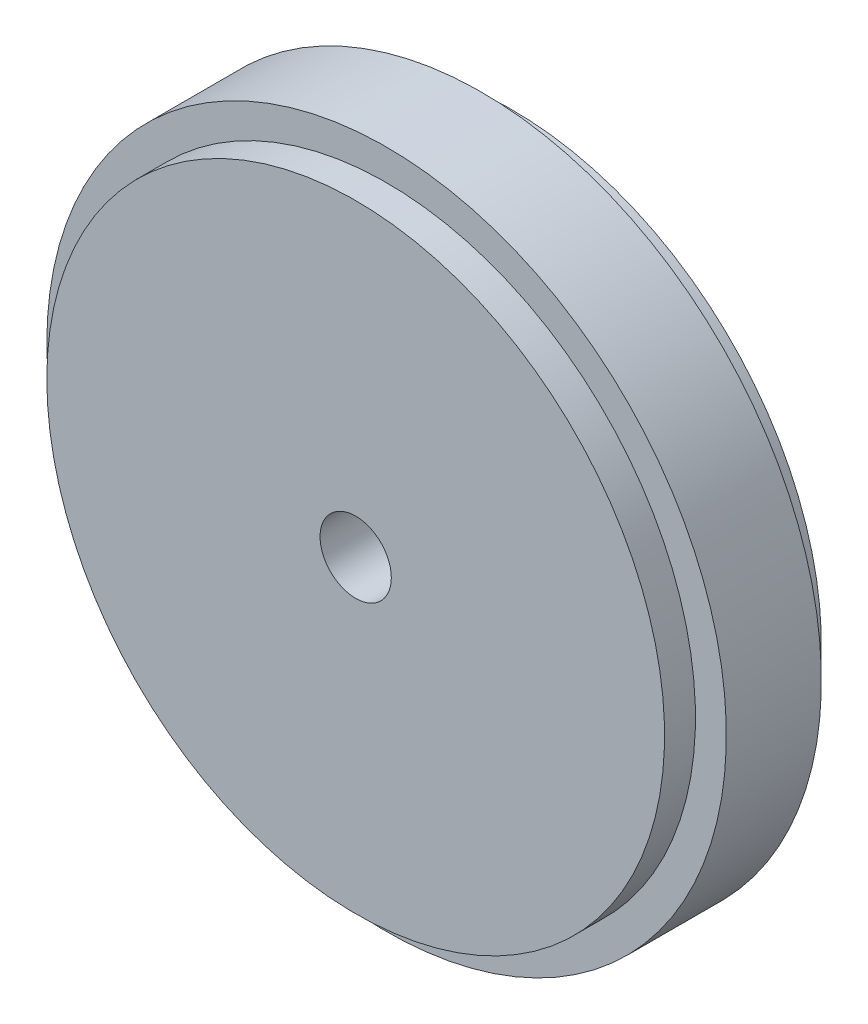
SolidWorks part; units mm, degrees
ref_plane "Front Plane" through (0, 0, 0) normal (0, 0, 1) x (1, 0, 0)
ref_plane "Top Plane" through (0, 0, 0) normal (0, 1, 0) x (1, 0, 0)
ref_plane "Right Plane" through (0, 0, 0) normal (1, 0, 0) x (0, 0, -1)
sketch "Sketch1" plane through (0, 0, 0) normal (1, 0, 0) x (0, 0, -1)
  line L0 (12.8177, 0) -> (-9.4475, 0) construction
  line L3 (1.3, 14.3) -> (5.3, 14.3)
  line L5 (1.3, 13) -> (1.3, 14.3)
  line L7 (6.6, 3.5) -> (6.6, 13)
  line L8 (6.6, 13) -> (5.3, 13)
  line L9 (0, 0) -> (0, 13)
  line L10 (0, 0) -> (8.6, 0)
  line L11 (0, 0) -> (0, 3.5)
  line L12 (6.6, 3.5) -> (8.6, 3.5)
  line L13 (8.6, 0) -> (8.6, 3.5)
  line L14 (1.3, 13) -> (0, 13)
  line L15 (5.3, 13) -> (5.3, 14.3)
  point P0 (1.3, 14.3428)
  point P17 (0, 0)
  point P18 (5.0988, 13)
  point P19 (3.152, 0)
  point P20 (0, 0)
  point P21 (0, 0)
  point P22 (-0.7374, 13)
  point P23 (9.324, 13)
  dimension "D1" = 0
  dimension "D2" = 4
  dimension "D3" = 6.6
  dimension "D4" = 13
  dimension "D5" = 1.3
  dimension "D6" = 8.6
  dimension "D7" = 3.5
  dimension "D8" = 14.3
revolve "Revolve1" add sketch "Sketch1" angle 360 about L0
sketch "Sketch3" plane through (0, 0, 0) normal (0, 0, 1) x (1, 0, 0)
  circle A0 centre (0, 0) radius 1.5
  dimension "D1" = 3
extrude "Cut-Extrude1" cut sketch "Sketch3" against normal through all
